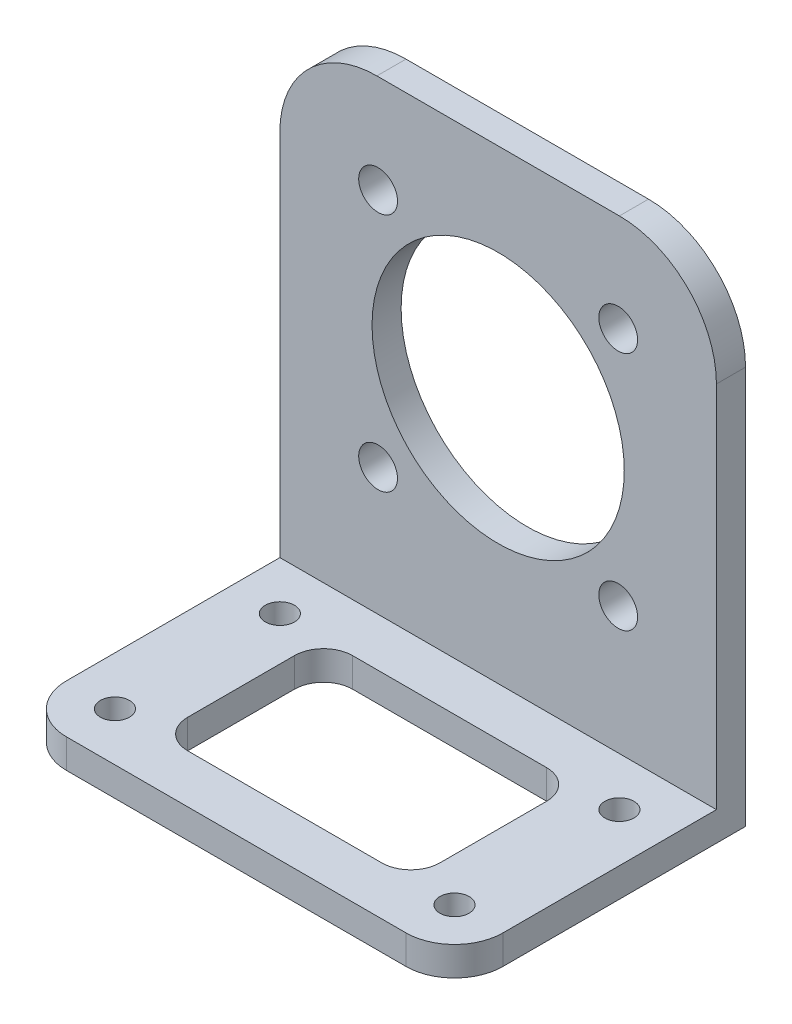
SolidWorks part; units mm, degrees
material "1060 合金"
ref_plane "前视基准面" through (0, 0, 0) normal (0, 0, 1) x (1, 0, 0)
ref_plane "上视基准面" through (0, 0, 0) normal (0, 1, 0) x (1, 0, 0)
ref_plane "右视基准面" through (0, 0, 0) normal (1, 0, 0) x (0, 0, -1)
sketch "草图1" plane through (0, 0, 0) normal (0, 0, 1) x (1, 0, 0)
  line L1 (-22.5, 25.5) -> (22.5, 25.5)
  line L2 (-22.5, 25.5) -> (-22.5, -25.5)
  line L3 (-22.5, -25.5) -> (22.5, -25.5)
  line L4 (22.5, 25.5) -> (22.5, -25.5)
  line L5 (-22.5, 25.5) -> (22.5, -25.5) construction
  line L6 (-22.5, -25.5) -> (22.5, 25.5) construction
  point P0 (0, 0)
  dimension "D1" = 51
  dimension "D2" = 45
extrude "凸台-拉伸1" add sketch "草图1" along normal blind 30
sketch "草图2" plane through (22.5, 0, 0) normal (1, 0, 0) x (0, 0, -1)
  line L1 (-30, 25.5) -> (-3, 25.5)
  line L2 (-30, 25.5) -> (-30, -22.5)
  line L3 (-30, -22.5) -> (-3, -22.5)
  line L4 (-3, 25.5) -> (-3, -22.5)
  dimension "D1" = 48
  dimension "D2" = 27
extrude "切除-拉伸1" cut sketch "草图2" against normal through all
sketch "草图3" plane through (0, -22.5, 0) normal (0, 1, 0) x (1, 0, 0)
  line L0 (-22.5, -30) -> (22.5, -30) construction
  line L2 (-22.5, -30) -> (-22.5, -3) construction
  line L3 (0, -3) -> (0, -30) construction
  line L4 (-22.5, -3) -> (22.5, -3) construction
  line L14 (-13, -8) -> (13, -8)
  line L15 (-13, -8) -> (-13, -25)
  line L16 (-13, -25) -> (13, -25)
  line L17 (13, -8) -> (13, -25)
  line L18 (-13, -8) -> (13, -25) construction
  line L19 (-13, -25) -> (13, -8) construction
  circle A0 centre (-17.5, -8) radius 1.5
  circle A1 centre (-17.5, -25) radius 1.5
  circle A2 centre (17.5, -25) radius 1.5
  circle A3 centre (17.5, -8) radius 1.5
  point P16 (0, -16.5)
  point P17 (0, -16.5)
  point P18 (0, -16.5)
  dimension "D1" = 3
  dimension "D2" = 3
  dimension "D3" = 5
  dimension "D4" = 17
  dimension "D5" = 5
  dimension "D6" = 5
  dimension "D7" = 17
  dimension "D8" = 26
extrude "切除-拉伸2" cut sketch "草图3" against normal through all
fillet "圆角1" radius 3 4 edges at (13, -24, 8) (13, -24, 25) (-13, -24, 25) (-13, -24, 8)
sketch "草图4" plane through (0, 0, 3) normal (0, 0, 1) x (1, 0, 0)
  line L0 (-22.5, -22.5) -> (22.5, -22.5) construction
  line L2 (22.5, -22.5) -> (22.5, 25.5) construction
  line L3 (17.5, 3) -> (0, 3) construction
  line L4 (0, 3) -> (12.3744, 15.3744) construction
  circle A0 centre (0, 3) radius 13
  circle A1 centre (0, 3) radius 17.5 construction
  circle A2 centre (12.3744, 15.3744) radius 2
  circle A3 centre (-12.3744, 15.3744) radius 2
  circle A4 centre (-12.3744, -9.3744) radius 2
  circle A5 centre (12.3744, -9.3744) radius 2
  point P19 (0, 3)
  dimension "D1" = 26
  dimension "D2" = 25.5
  dimension "D3" = 22.5
  dimension "D4" = 35
  dimension "D6" = 4
  dimension "D5" = 45
  dimension "D7" = 4
extrude "切除-拉伸3" cut sketch "草图4" against normal blind 30
fillet "圆角2" radius 10 2 edges at (22.5, 25.5, 1.5) (-22.5, 25.5, 1.5)
fillet "圆角3" radius 5 2 edges at (-22.5, -24, 30) (22.5, -24, 30)
